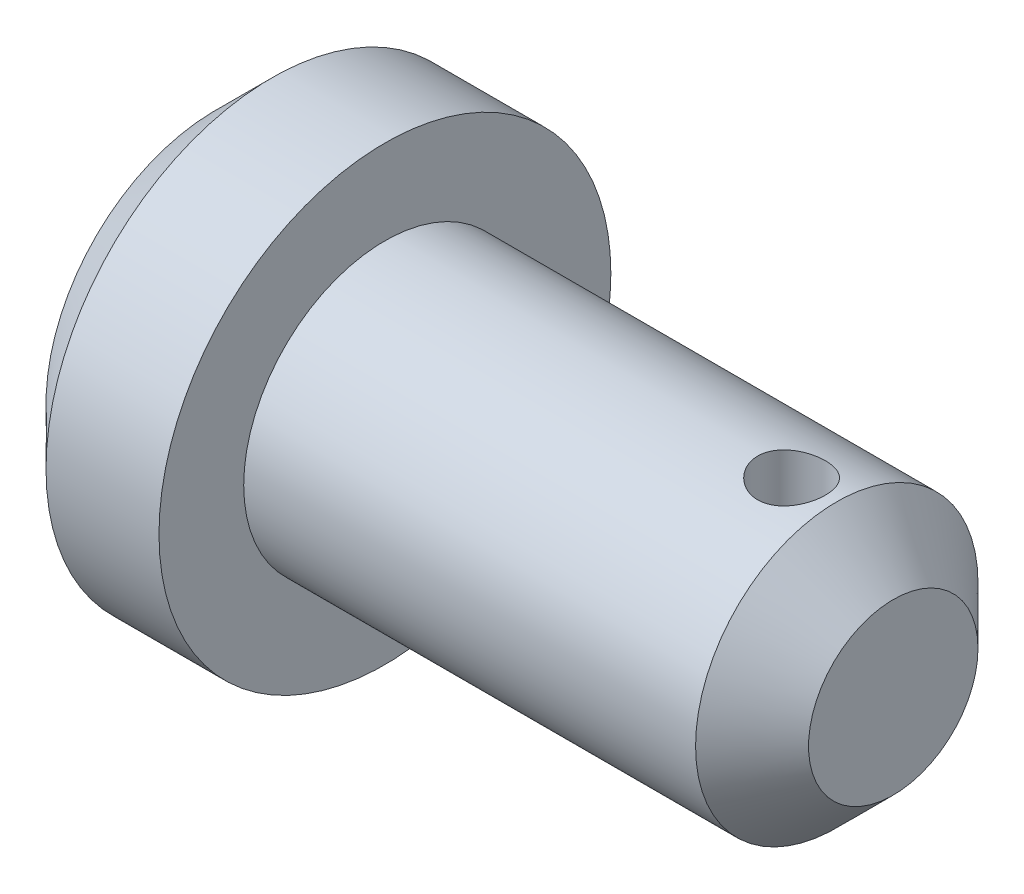
SolidWorks part; units mm, degrees
ref_plane "前基準面" through (0, 0, 0) normal (0, 0, 1) x (1, 0, 0)
ref_plane "上基準面" through (0, 0, 0) normal (0, 1, 0) x (1, 0, 0)
ref_plane "右基準面" through (0, 0, 0) normal (1, 0, 0) x (0, 0, -1)
ref_plane "平面1"
sketch "草圖1" plane through (0, 0, 0) normal (0, 0, 1) x (1, 0, 0)
  line L0 (0, 0) -> (-120, 0)
  line L1 (-120, 0) -> (-120, 30)
  line L2 (-120, 30) -> (-110, 40)
  line L3 (-110, 40) -> (-90, 40)
  line L4 (-90, 40) -> (-90, 25)
  line L5 (-90, 25) -> (-10, 25)
  line L6 (-10, 25) -> (0, 15)
  line L7 (0, 15) -> (0, 0)
  line L8 (0, 0) -> (-120, 0) construction
  dimension "D1" = 120
  dimension "D2" = 15
  dimension "D3" = 25
  dimension "D4" = 90
  dimension "D5" = 40
  dimension "D6" = 135
  dimension "D7" = 225
revolve "迴轉1" add sketch "草圖1" angle 360 about L8
ref_plane "平面2"
sketch "草圖2" plane through (0, 0, 0) normal (0, 0, 1) x (1, 0, 0)
  line L0 (-18, 33) -> (-24, 33)
  line L1 (-24, 33) -> (-24, -51)
  line L2 (-24, -51) -> (-18, -51)
  line L3 (-18, -51) -> (-18, 33)
  line L4 (-18, -51) -> (-18, 33) construction
  dimension "D1" = 6
revolve "迴轉2" cut sketch "草圖2" angle 360 about L4
